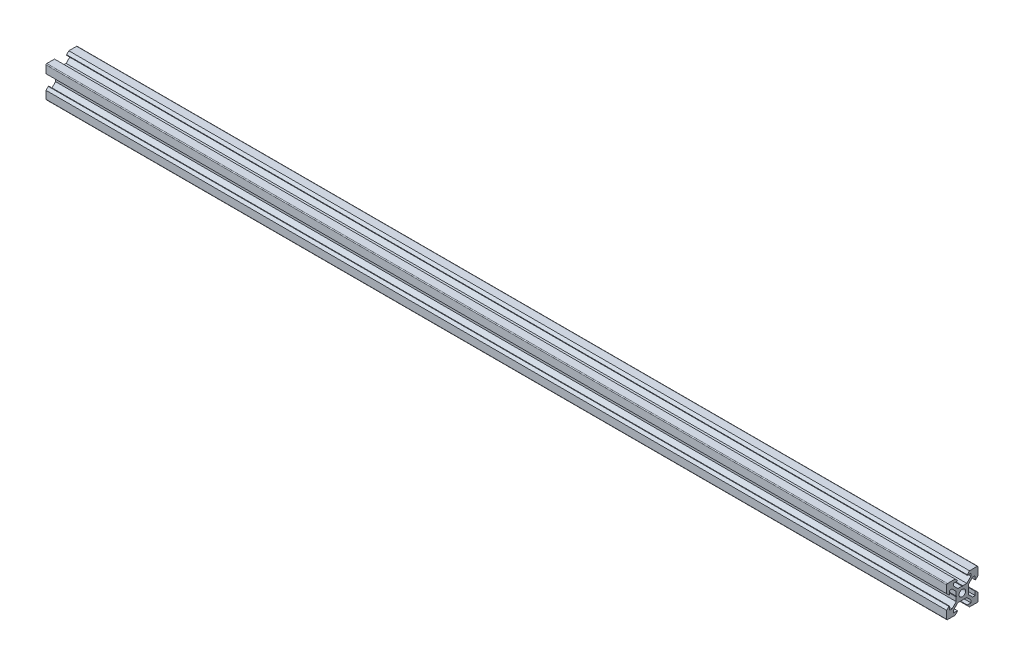
SolidWorks part; units mm, degrees
material "6061-T6 (SS)"
ref_plane "Top" through (0, 0, 0) normal (0, 0, 1) x (1, 0, 0)
ref_plane "Front" through (0, 0, 0) normal (0, 1, 0) x (1, 0, 0)
ref_plane "Right" through (0, 0, 0) normal (1, 0, 0) x (0, 0, -1)
sketch "Profile Sketch" plane through (0, 0, 0) normal (1, 0, 0) x (0, 0, -1)
  line L0 (-0.5, 10) -> (-5.42, 10)
  line L1 (-4.5, 8.2) -> (-4.5, 6.56)
  line L2 (-4.5, 6.56) -> (-7.16, 3.9)
  line L3 (-7.16, 3.9) -> (-9.79, 3.9)
  line L4 (-9.79, 3.9) -> (-10, 3.69)
  line L7 (-3.4387, 5.5) -> (-6.1, 2.8387)
  line L8 (-6.1, 2.8387) -> (-6.1, -0.21)
  line L9 (-6.875, 8.545) -> (-6.875, 8.2)
  line L10 (-6.875, 8.2) -> (-4.5, 8.2)
  line L11 (-6.875, 8.545) -> (-5.42, 10)
  line L12 (0, -10) -> (0, 10) construction
  line L13 (-20, 0) -> (20, 0) construction
  line L14 (-10, -10) -> (-10, 10) construction
  line L15 (-6.875, -8.545) -> (-5.42, -10)
  line L16 (-6.875, -8.2) -> (-4.5, -8.2)
  line L17 (-6.875, -8.545) -> (-6.875, -8.2)
  line L18 (-3.44, -5.5) -> (-6.1, -2.8387)
  line L21 (-7.16, -3.9) -> (-9.79, -3.9)
  line L22 (-4.5, -6.56) -> (-7.16, -3.9)
  line L23 (-4.5, -8.2) -> (-4.5, -6.56)
  line L24 (-0.5, -10) -> (-5.42, -10)
  line L25 (-10, 0) -> (-20, 10) construction
  line L26 (-18.545, 3.125) -> (-18.2, 3.125)
  line L27 (-13.125, -8.545) -> (-13.125, -8.2)
  line L28 (-13.125, -8.2) -> (-15.5, -8.2)
  line L29 (-13.125, -8.545) -> (-14.58, -10)
  line L30 (-15.5, -8.2) -> (-15.5, -6.56)
  line L31 (-15.5, -6.56) -> (-12.84, -3.9)
  line L32 (-12.84, -3.9) -> (-10.21, -3.9)
  line L33 (-20, 4.58) -> (-20, 9.5)
  line L34 (-13.9, 2.8387) -> (-13.9, 0.21)
  line L35 (-16.56, 5.5) -> (-13.9, 2.8387)
  line L36 (-12.84, 3.9) -> (-10.21, 3.9)
  line L37 (-15.5, 6.56) -> (-12.84, 3.9)
  line L38 (-15.5, 8.2) -> (-15.5, 6.56)
  line L39 (-13.125, 8.545) -> (-14.58, 10)
  line L40 (-13.125, 8.2) -> (-15.5, 8.2)
  line L41 (-13.125, 8.545) -> (-13.125, 8.2)
  line L42 (-18.2, 3.125) -> (-18.2, 5.5)
  line L43 (-18.545, 3.125) -> (-20, 4.58)
  line L44 (-18.2, 5.5) -> (-16.56, 5.5)
  line L45 (-14.58, 10) -> (-19.5, 10)
  line L46 (-16.56, -5.5) -> (-13.9, -2.8387)
  line L47 (-14.58, -10) -> (-19.5, -10)
  line L48 (-18.2, -5.5) -> (-16.56, -5.5)
  line L49 (-18.545, -3.125) -> (-20, -4.58)
  line L50 (-18.2, -3.125) -> (-18.2, -5.5)
  line L51 (-20, -4.58) -> (-20, -9.5)
  line L52 (-18.545, -3.125) -> (-18.2, -3.125)
  line L53 (10, -10) -> (10, 10) construction
  line L99 (-10, 3.69) -> (-10.21, 3.9)
  line L100 (-10, -3.69) -> (-10.21, -3.9)
  line L101 (-9.79, -3.9) -> (-10, -3.69)
  line L102 (-13.9, -0.21) -> (-13.69, 0)
  line L103 (-13.69, 0) -> (-13.9, 0.21)
  line L104 (-13.9, -0.21) -> (-13.9, -2.8387)
  line L105 (-6.1, -0.21) -> (-6.31, 0)
  line L106 (-6.31, 0) -> (-6.1, -0.21)
  line L107 (-6.1, -0.21) -> (-6.1, -2.8387)
  line L117 (-5.42, -10) -> (-0.5, -10)
  line L118 (20, -10) -> (20, 10) construction
  line L119 (20, -10) -> (-20, -10) construction
  line L120 (-20, -10) -> (-20, 10) construction
  line L121 (20, 10) -> (-20, 10) construction
  line L122 (20, -10) -> (-20, 10) construction
  line L123 (-20, -10) -> (20, 10) construction
  line L124 (-5.42, 10) -> (-0.5, 10)
  line L125 (-1.455, 3.125) -> (-1.8, 3.125)
  line L126 (-1.455, -3.125) -> (-1.8, -3.125)
  line L127 (-1.8, -5.5) -> (-3.44, -5.5)
  line L128 (-1.8, 5.5) -> (-3.44, 5.5)
  line L129 (-1.8, 3.125) -> (-1.8, 5.5)
  line L130 (-1.8, -3.125) -> (-1.8, -5.5)
  line L131 (0, -4.58) -> (0, -9.5)
  line L132 (0, 4.58) -> (0, 9.5)
  line L133 (-1.455, 3.125) -> (0, 4.58)
  line L134 (-1.455, -3.125) -> (0, -4.58)
  circle A0 centre (-10, 0) radius 2.1
  arc A1 (-19.5, 10) -> (-20, 9.5) centre (-19.5, 9.5) ccw
  arc A2 (-19.5, -10) -> (-20, -9.5) centre (-19.5, -9.5) cw
  arc A3 (-0.5, -10) -> (0, -9.5) centre (-0.5, -9.5) ccw
  arc A4 (-0.5, 10) -> (0, 9.5) centre (-0.5, 9.5) cw
  point P2 (-17.38, 5.5)
  point P35 (-2.4957, 0)
  point P76 (-2.62, 5.5)
  point P108 (0, -8.2)
  point P119 (0, 8.2)
  point P131 (0, 0)
  point P143 (0, 0)
  dimension "D4" = 5.42
  dimension "D5" = 40
  dimension "D6" = 4.2
  dimension "D16" = 0.5
  dimension "D1" = 0.21
  dimension "D2" = 45
  dimension "D3" = 20
  dimension "D7" = 1.5
  dimension "D8" = 1.8
  dimension "D9" = 10
  dimension "D10" = 3.9
  dimension "D11" = 3.9
  dimension "D13" = 3.125
  dimension "D14" = 5.5
  dimension "D15" = 1.64
extrude "Profile Extrude" add sketch "Profile Sketch" along normal blind 575
equation "\"M8x1.25_Close_Hole\"= 8.4"
